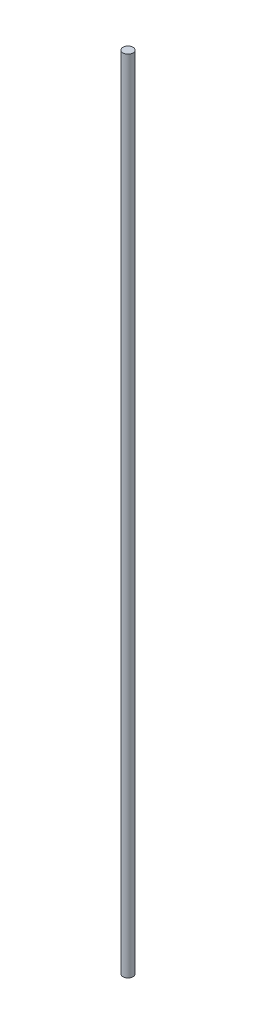
SolidWorks part; units mm, degrees
material "Thornel Mat VMA"
ref_plane "前视基准面" through (0, 0, 0) normal (0, 0, 1) x (1, 0, 0)
ref_plane "上视基准面" through (0, 0, 0) normal (0, 1, 0) x (1, 0, 0)
ref_plane "右视基准面" through (0, 0, 0) normal (1, 0, 0) x (0, 0, -1)
sketch "草图1" plane through (0, 0, 0) normal (0, 1, 0) x (1, 0, 0)
  circle A0 centre (0, 0) radius 0.5
  dimension "D1" = 1
extrude "凸台-拉伸1" add sketch "草图1" along normal blind 80
equation "\"m\"= 2"
